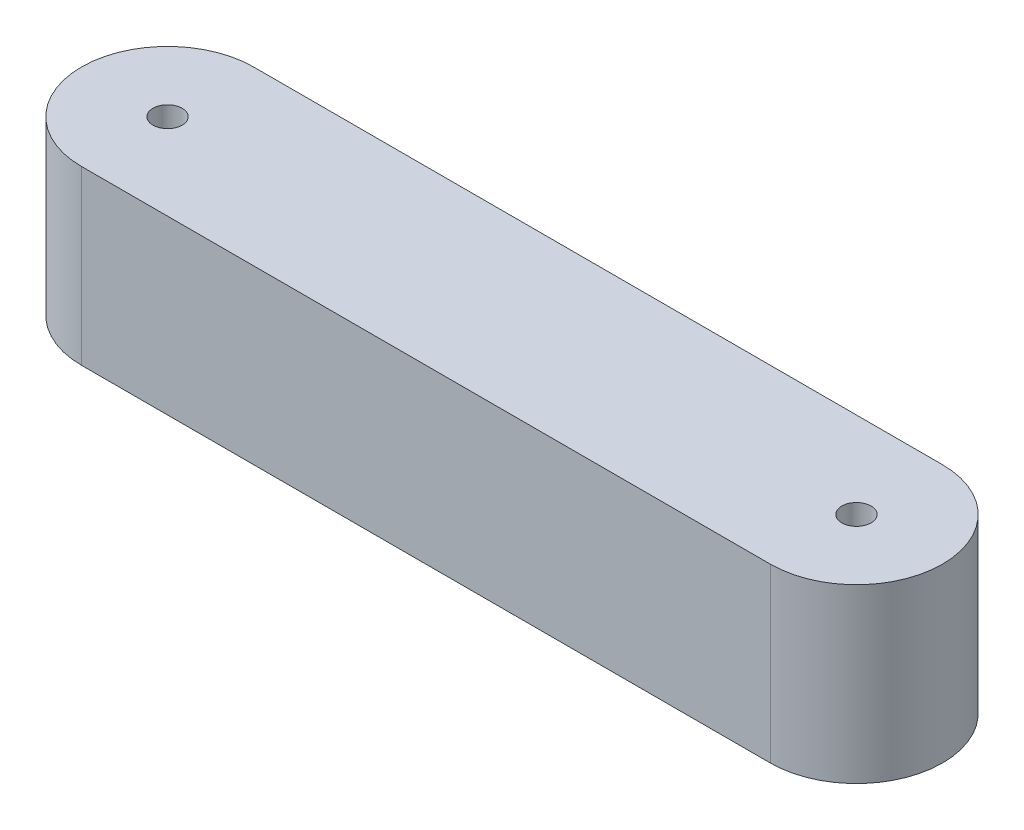
SolidWorks part; units mm, degrees
material "ESUN PLA +"
ref_plane "Front Plane" through (0, 0, 0) normal (0, 0, 1) x (1, 0, 0)
ref_plane "Top Plane" through (0, 0, 0) normal (0, 1, 0) x (1, 0, 0)
ref_plane "Right Plane" through (0, 0, 0) normal (1, 0, 0) x (0, 0, -1)
sketch "Sketch1" plane through (0, 0, 0) normal (0, 1, 0) x (1, 0, 0)
  line L0 (-40, 0) -> (40, 0) construction
  line L1 (-40, 10) -> (40, 10)
  line L2 (-40, -10) -> (40, -10)
  arc A0 (-40, 10) -> (-40, -10) centre (-40, 0) ccw
  arc A1 (40, -10) -> (40, 10) centre (40, 0) ccw
  circle A2 centre (-40, 0) radius 1.7
  circle A3 centre (40, 0) radius 1.7
  point P2 (0, 0)
  dimension "D3" = 3.4
  dimension "D1" = 20
  dimension "D2" = 80
extrude "Boss-Extrude1" add sketch "Sketch1" along normal blind 20
